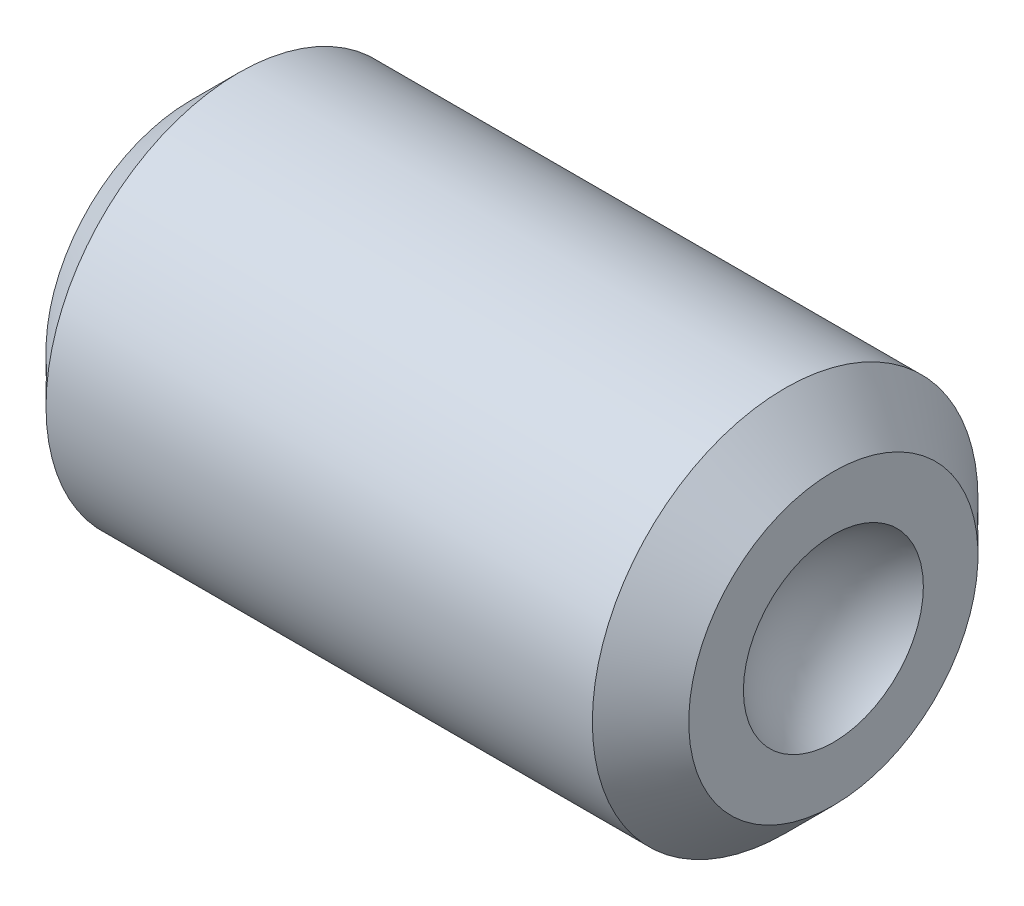
SolidWorks part; units mm, degrees
ref_plane "Front Plane" through (0, 0, 0) normal (0, 0, 1) x (1, 0, 0)
ref_plane "Top Plane" through (0, 0, 0) normal (0, 1, 0) x (1, 0, 0)
ref_plane "Right Plane" through (0, 0, 0) normal (1, 0, 0) x (0, 0, -1)
sketch "Sketch1" plane through (0, 0, 0) normal (0, 0, 1) x (1, 0, 0)
  line L0 (0, 0) -> (0, 1.125)
  line L1 (0, 1.125) -> (0.375, 1.5)
  line L2 (0.375, 1.5) -> (4.625, 1.5)
  line L3 (4.625, 1.5) -> (5, 1.125)
  line L4 (0, 0) -> (4.625, 0) construction
  line L5 (0.375, 1.5) -> (0.375, 1.125) construction
  line L6 (0.375, 1.125) -> (0.375, 0.75) construction
  line L7 (0.375, 0.75) -> (0.375, 0.375) construction
  line L8 (0.375, 0.375) -> (0.375, 0) construction
  line L9 (0.375, 1.125) -> (0, 1.125) construction
  line L10 (4.625, 1.5) -> (4.625, 0) construction
  line L11 (5, 1.125) -> (5, 0.7)
  line L12 (0, 0) -> (4.625, 0)
  arc A0 (4.625, 0) -> (5, 0.7) centre (5.4658, 0) cw
  dimension "D1" = 45
  dimension "D2" = 3
  dimension "D3" = 5
  dimension "D4" = 1.4
revolve "Revolve1" add sketch "Sketch1" angle 360 about L12
sketch "Sketch2" plane through (0, 0, 0) normal (-1, 0, 0) x (0, 0, 1)
  line L1 (0, 0.866) -> (-0.75, 0.433)
  line L2 (-0.75, 0.433) -> (-0.75, -0.433)
  line L3 (-0.75, -0.433) -> (0, -0.866)
  line L4 (0, -0.866) -> (0.75, -0.433)
  line L5 (0.75, -0.433) -> (0.75, 0.433)
  line L6 (0.75, 0.433) -> (0, 0.866)
  circle A0 centre (0, 0) radius 0.75 construction
  dimension "D1" = 1.5
extrude "Cut-Extrude1" cut sketch "Sketch2" against normal offset from surface (3 mm away) 2 up to face at (5, -1.125, 0)
